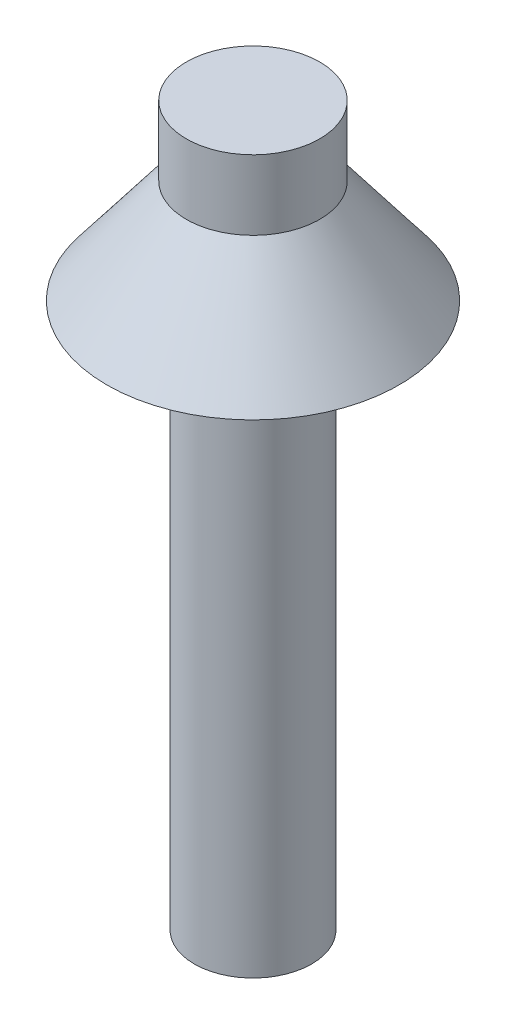
SolidWorks part; units mm, degrees
ref_plane "Piano frontale" through (0, 0, 0) normal (0, 0, 1) x (1, 0, 0)
ref_plane "Piano superiore" through (0, 0, 0) normal (0, 1, 0) x (1, 0, 0)
ref_plane "Piano destro" through (0, 0, 0) normal (1, 0, 0) x (0, 0, -1)
sketch "Schizzo2" plane through (0, 0, 0) normal (0, 1, 0) x (1, 0, 0)
  circle A0 centre (0, 0) radius 30
  dimension "D1" = 60
extrude "Estrusione-Estrusione1" add sketch "Schizzo2" along normal blind 319
sketch "Schizzo4" plane through (0, 0, 0) normal (0, 0, 1) x (1, 0, 0)
  line L0 (30, 319) -> (-30, 319) construction
  line L1 (0, 367.6592) -> (34.1087, 367.6592)
  line L4 (34.1087, 367.6592) -> (34.1087, 331.9614)
  line L7 (34.1087, 331.9614) -> (74.7591, 278.9392)
  line L8 (74.7591, 278.9392) -> (0, 278.9392)
  line L9 (0, 278.9392) -> (0, 367.6592)
  point P0 (0, 319)
revolve "Rivoluzione1" add sketch "Schizzo4" angle 360 about L9
